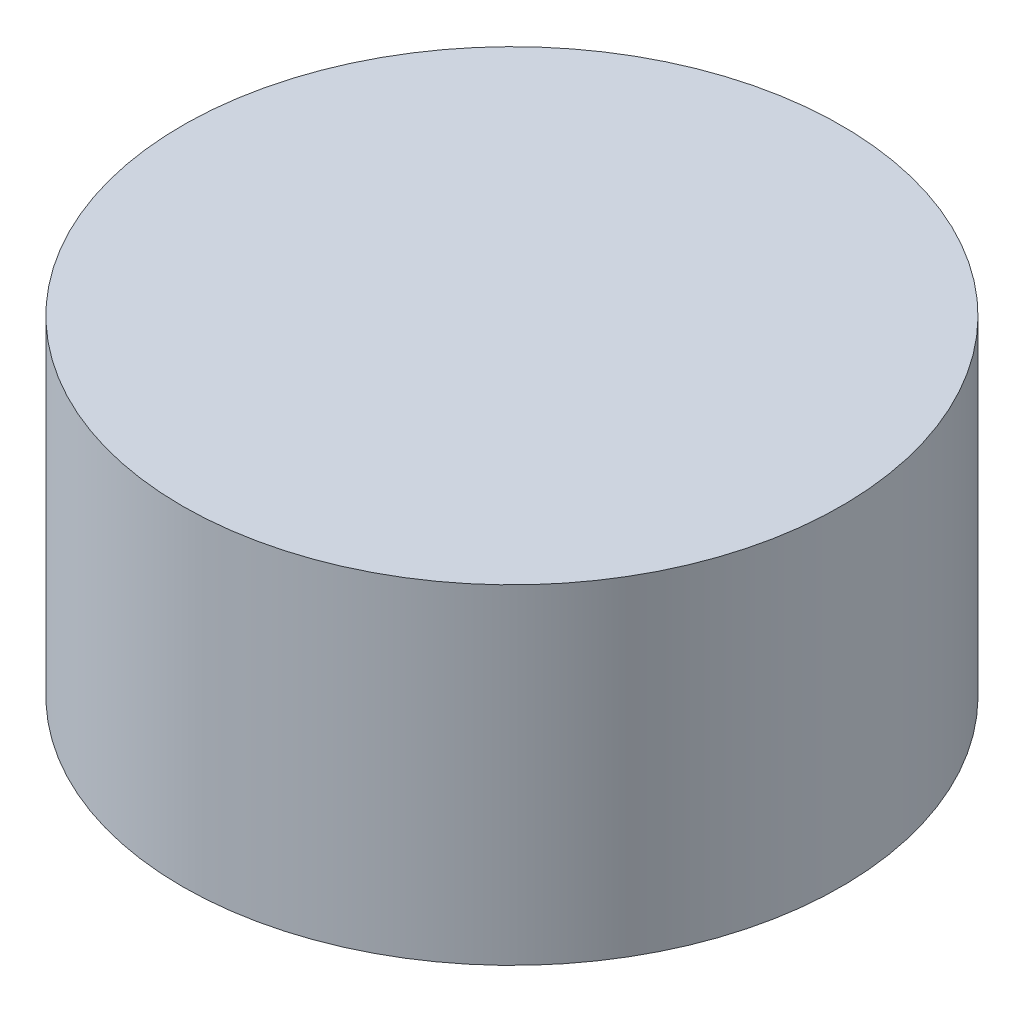
SolidWorks part; units mm, degrees
material "Plastique personnalisé"
ref_plane "Plan de face" through (0, 0, 0) normal (0, 0, 1) x (1, 0, 0)
ref_plane "Plan de dessus" through (0, 0, 0) normal (0, 1, 0) x (1, 0, 0)
ref_plane "Plan de droite" through (0, 0, 0) normal (1, 0, 0) x (0, 0, -1)
sketch "Esquisse1" plane through (0, 0, 0) normal (0, 1, 0) x (1, 0, 0)
  circle A0 centre (0, 0) radius 46
  dimension "D1" = 92
extrude "Boss.-Extru.1" add sketch "Esquisse1" along normal blind 46
